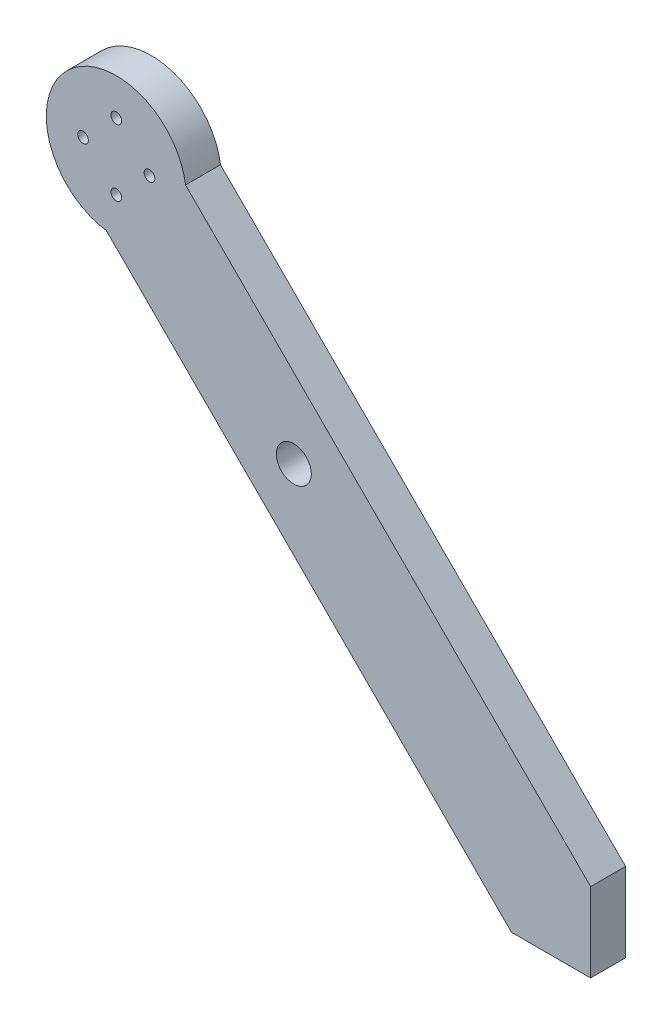
SolidWorks part; units mm, degrees
ref_plane "Plan de face" through (0, 0, 0) normal (0, 0, 1) x (1, 0, 0)
ref_plane "Plan de dessus" through (0, 0, 0) normal (0, 1, 0) x (1, 0, 0)
ref_plane "Plan de droite" through (0, 0, 0) normal (1, 0, 0) x (0, 0, -1)
sketch "Esquisse1" plane through (0, 0, 0) normal (0, 0, 1) x (1, 0, 0)
  line L0 (-22.6274, 0) -> (0, 0)
  line L1 (0, 0) -> (0, 22.6274)
  line L2 (32.3726, 55) -> (0, 22.6274) construction
  line L3 (0, 22.6274) -> (-32.3726, 55)
  line L4 (-32.3726, 55) -> (-124.2965, 146.9239)
  line L5 (-124.2965, 146.9239) -> (-146.9239, 124.2965)
  line L6 (-146.9239, 124.2965) -> (-55, 32.3726)
  line L7 (-55, 32.3726) -> (-22.6274, 0)
  line L8 (-32.3726, 55) -> (-55, 32.3726) construction
  circle A0 centre (-135.6102, 135.6102) radius 20
  dimension "D2" = 40
  dimension "D1" = 130
extrude "Boss.-Extru.1" add sketch "Esquisse1" along normal blind 10 contours A0 L6 L7 L0 L1 L3 L4 | L6 A0 L4 L5 | L4 A0 L6 L5
sketch "Esquisse2" plane through (0, 0, 0) normal (0, 0, -1) x (-1, 0, 0)
  circle A3 centre (31.8198, 31.8198) radius 4.5
  circle A4 centre (14.1421, 14.1421) radius 4.5
  dimension "D1" = 9
  dimension "D2" = 9
extrude "Boss.-Extru.2" add sketch "Esquisse2" along normal up to surface (5 mm away)
sketch "Esquisse3" plane through (0, 0, 0) normal (0, 0, -1) x (-1, 0, 0)
  line L0 (135.6102, 135.6102) -> (149.7523, 149.7523) construction
  line L1 (135.6102, 135.6102) -> (135.6102, 145.1102) construction
  line L2 (135.6102, 135.6102) -> (135.6102, 145.1102) construction
  line L3 (135.6102, 135.6102) -> (145.1102, 135.6102) construction
  circle A0 centre (135.6102, 135.6102) radius 9.5 construction
  arc A1 (138.4386, 115.8112) -> (115.8112, 138.4386) centre (135.6102, 135.6102) ccw construction
  circle A2 centre (135.6102, 145.1102) radius 1.525
  circle A3 centre (145.1102, 135.6102) radius 1.525
  circle A4 centre (135.6102, 126.1102) radius 1.525
  circle A5 centre (126.1102, 135.6102) radius 1.525
  circle A6 centre (84.8528, 84.8528) radius 5
  dimension "D1" = 19
  dimension "D3" = 3.05
  dimension "D6" = 10
  dimension "D2" = 45
  dimension "D5" = 90
  dimension "D7" = 120
  dimension "D4" = 4
extrude "Enlèv. mat.-Extru.1" cut sketch "Esquisse3" against normal through all
